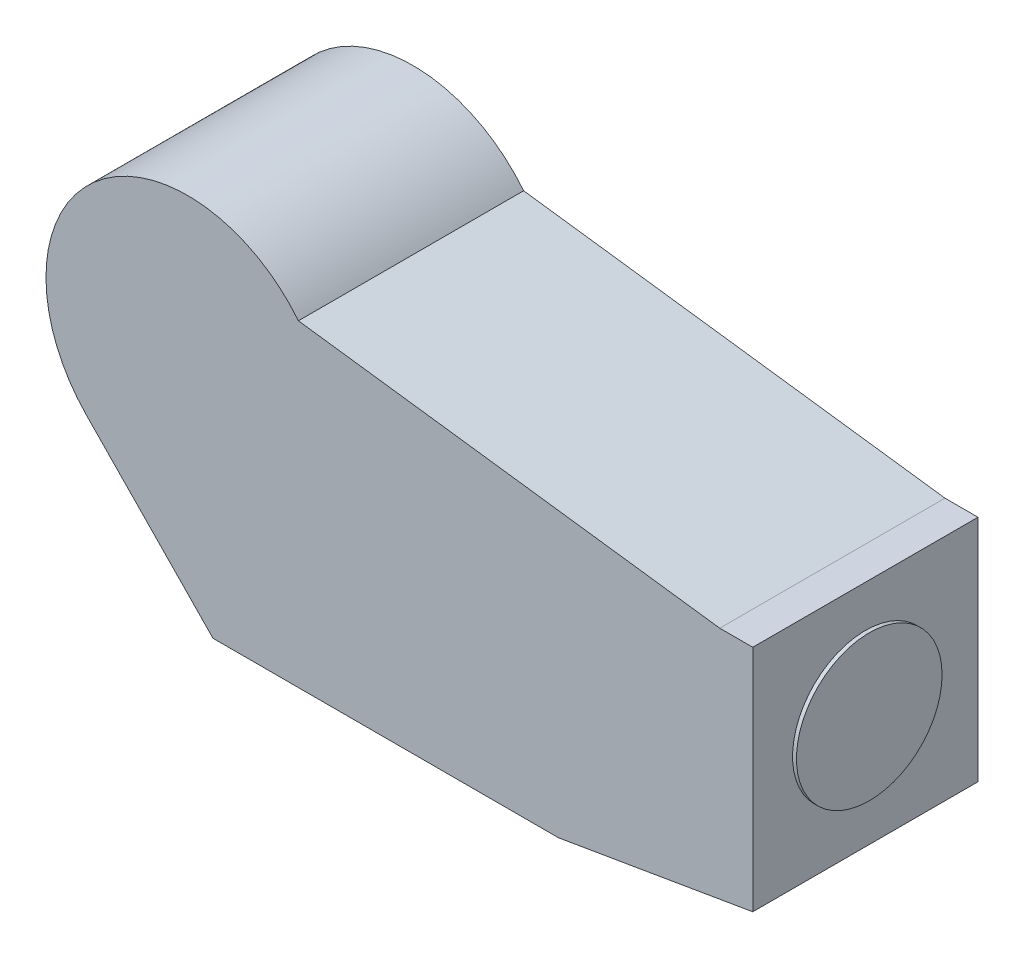
SolidWorks part; units mm, degrees
ref_plane "Front Plane" through (0, 0, 0) normal (0, 0, 1) x (1, 0, 0)
ref_plane "Top Plane" through (0, 0, 0) normal (0, 1, 0) x (1, 0, 0)
ref_plane "Right Plane" through (0, 0, 0) normal (1, 0, 0) x (0, 0, -1)
sketch "Sketch1" plane through (0, 0, 0) normal (0, 0, 1) x (1, 0, 0)
  line L0 (0, 0) -> (291, 0) construction
  line L1 (291, 0) -> (291, 17)
  line L2 (291, 17) -> (274, 17)
  line L3 (274, 17) -> (57, 45.607)
  line L4 (291, 0) -> (291, -101)
  line L5 (291, -101) -> (191, -118)
  line L6 (191, -118) -> (13, -118)
  line L7 (13, -118) -> (-52.3049, -50.9234)
  arc A0 (57, 45.607) -> (-52.3049, -50.9234) centre (0, 0) ccw
  dimension "D1" = 146
  dimension "D2" = 291
  dimension "D3" = 217
  dimension "D4" = 17
  dimension "D5" = 17
  dimension "D6" = 101
  dimension "D7" = 100
  dimension "D8" = 118
  dimension "D9" = 178
extrude "Boss-Extrude1" add sketch "Sketch1" along normal mid plane 116
sketch "Sketch2" plane through (291, 0, 0) normal (1, 0, 0) x (0, 0, -1)
  line L0 (-58, -101) -> (-58, 17) construction
  circle A0 centre (0, -42) radius 37.5
  point P2 (0, 0)
  point P6 (-58, -42)
  dimension "D1" = 75
extrude "Boss-Extrude2" add sketch "Sketch2" along normal blind 2
